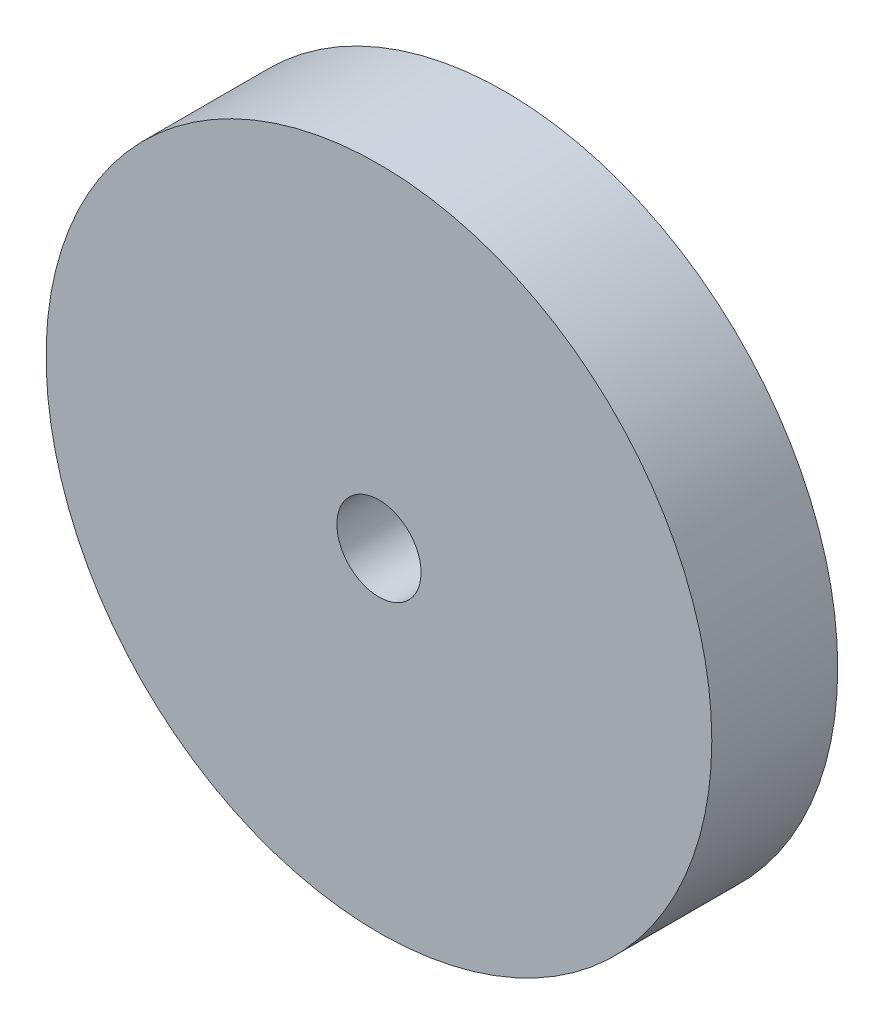
SolidWorks part; units mm, degrees
ref_plane "Front Plane" through (0, 0, 0) normal (0, 0, 1) x (1, 0, 0)
ref_plane "Top Plane" through (0, 0, 0) normal (0, 1, 0) x (1, 0, 0)
ref_plane "Right Plane" through (0, 0, 0) normal (1, 0, 0) x (0, 0, -1)
sketch "Sketch1" plane through (0, 0, 0) normal (0, 0, 1) x (1, 0, 0)
  circle A0 centre (0, 0) radius 14.7703
  circle A1 centre (0, 0) radius 1.8669
  dimension "D1" = 29.5406
  dimension "D2" = 3.7338
extrude "Boss-Extrude1" add sketch "Sketch1" along normal blind 5.588
